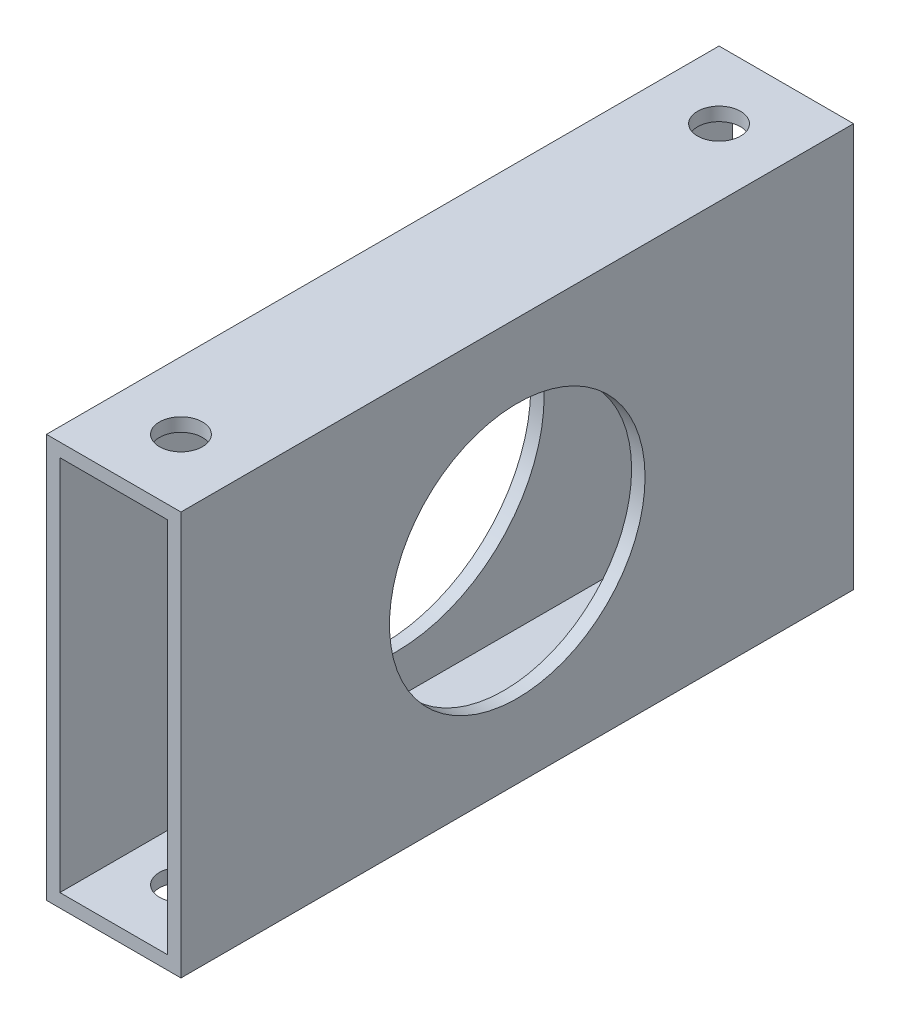
SolidWorks part; units mm, degrees
material "6061 合金"
ref_plane "正面" through (0, 0, 0) normal (0, 0, 1) x (1, 0, 0)
ref_plane "平面" through (0, 0, 0) normal (0, 1, 0) x (1, 0, 0)
ref_plane "右側面" through (0, 0, 0) normal (1, 0, 0) x (0, 0, -1)
sketch "断面" plane through (0, 0, 0) normal (0, 0, 1) x (1, 0, 0)
  line L1 (-5, -15) -> (5, -15)
  line L2 (-5, -15) -> (-5, 15)
  line L3 (-5, 15) -> (5, 15)
  line L4 (5, -15) -> (5, 15)
  line L5 (-5, -15) -> (5, 15) construction
  line L6 (-5, 15) -> (5, -15) construction
  point P0 (0, 0)
  dimension "D1" = 30
  dimension "D2" = 10
extrude "フレーム全長" add sketch "断面" along normal blind 50 thin thin type one direction reverse wall 1
sketch "上面穴スケッチ" plane through (0, 15, 0) normal (0, 1, 0) x (1, 0, 0)
  line L0 (0, 0) -> (0, -50) construction
  line L1 (5, 0) -> (-5, 0) construction
  line L2 (5, -50) -> (-5, -50) construction
  line L3 (-5, -25) -> (5, -25) construction
  line L4 (-5, -50) -> (-5, 0) construction
  line L5 (5, -50) -> (5, 0) construction
  line L6 (-3, -50) -> (-3, 0) construction
  line L7 (-1, -50) -> (-1, 0) construction
  line L8 (1, -50) -> (1, 0) construction
  line L9 (3, -50) -> (3, 0) construction
  circle A0 centre (0, -5) radius 1.6
  circle A1 centre (0, -45) radius 1.6
  point P14 (-3, -25)
  point P15 (-1, -25)
  point P16 (1, -25)
  point P17 (3, -25)
  point P21 (-3, -25)
  point P24 (-1, -25)
  point P27 (1, -25)
  point P30 (3, -25)
  dimension "D1" = 5
  dimension "D2" = 3.2
sketch "側面穴スケッチ" plane through (5, 0, 0) normal (1, 0, 0) x (0, 0, -1)
  line L0 (0, 0) -> (-50, 0) construction
  line L1 (0, -15) -> (0, 15) construction
  line L2 (-50, -15) -> (-50, 15) construction
  line L3 (-25, 15) -> (-25, -15) construction
  line L4 (-50, 15) -> (0, 15) construction
  line L5 (-50, -15) -> (0, -15) construction
  line L6 (-50, 9) -> (0, 9) construction
  line L7 (-50, 3) -> (0, 3) construction
  line L8 (-50, -3) -> (0, -3) construction
  line L9 (-50, -9) -> (0, -9) construction
  circle A0 centre (-25, 0) radius 9.5
  point P14 (-25, 9)
  point P15 (-25, 3)
  point P16 (-25, -3)
  point P17 (-25, -9)
  point P21 (-25, 9)
  point P24 (-25, 3)
  point P27 (-25, -3)
  point P30 (-25, -9)
  dimension "D1" = 19
extrude "上面穴貫通" cut sketch "上面穴スケッチ" against normal through all
extrude "側面穴貫通" cut sketch "側面穴スケッチ" against normal through all
sketch "ｽｹｯﾁ1" plane through (-5, 0, 0) normal (-1, 0, 0) x (0, 0, 1)
  circle A0 centre (25, 0) radius 11
  dimension "D1" = 22
extrude "ｶｯﾄ - 押し出し1" cut sketch "ｽｹｯﾁ1" against normal up to next
